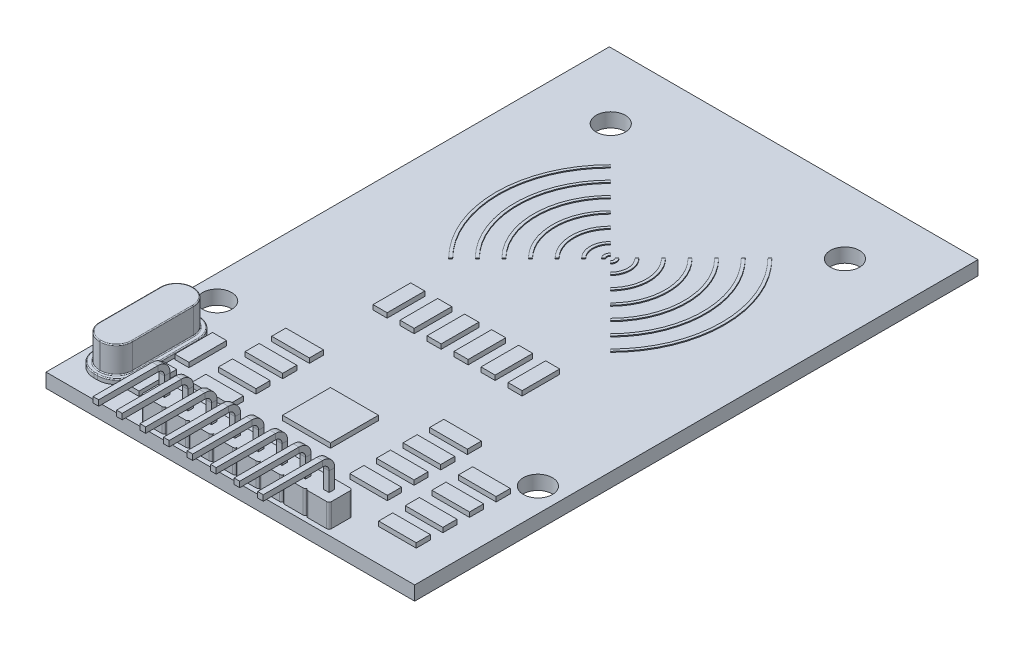
SolidWorks part; units mm, degrees
ref_plane "Front Plane" through (0, 0, 0) normal (0, 0, 1) x (1, 0, 0)
ref_plane "Top Plane" through (0, 0, 0) normal (0, 1, 0) x (1, 0, 0)
ref_plane "Right Plane" through (0, 0, 0) normal (1, 0, 0) x (0, 0, -1)
sketch "Sketch1" plane through (0, 0, 0) normal (0, 1, 0) x (1, 0, 0)
  line L1 (-19.6, 29.95) -> (19.6, 29.95)
  line L2 (-19.6, 29.95) -> (-19.6, -29.95)
  line L3 (-19.6, -29.95) -> (19.6, -29.95)
  line L4 (19.6, 29.95) -> (19.6, -29.95)
  line L5 (-19.6, 29.95) -> (19.6, -29.95) construction
  line L6 (-19.6, -29.95) -> (19.6, 29.95) construction
  point P0 (0, 0)
  dimension "D1" = 39.2
  dimension "D2" = 59.9
extrude "Boss-Extrude1" add sketch "Sketch1" along normal blind 1.5
sketch "Sketch3" plane through (0, 1.5, 0) normal (0, 1, 0) x (1, 0, 0)
  line L0 (0, 29.95) -> (0, -29.95) construction
  line L2 (19.6, 29.95) -> (-19.6, 29.95) construction
  line L3 (-17.05, -14.3) -> (17.05, -14.3) construction
  line L4 (-12.45, 22.95) -> (12.45, 22.95) construction
  line L5 (-19.6, -29.95) -> (19.6, -29.95) construction
  circle A0 centre (12.45, 22.95) radius 1.55
  circle A1 centre (-12.45, 22.95) radius 1.55
  circle A2 centre (17.05, -14.3) radius 1.55
  circle A3 centre (-17.05, -14.3) radius 1.55
  point P16 (0, 22.95)
  point P17 (0, -14.3)
  dimension "D1" = 3.1
  dimension "D2" = 12.45
  dimension "D3" = 7
  dimension "D6" = 17.05
  dimension "D7" = 15.65
extrude "Cut-Extrude1" cut sketch "Sketch3" against normal up to surface (1.5 mm away) up to face at (0, 0, 0)
sketch "Sketch4" plane through (0, 1.5, 0) normal (0, 1, 0) x (1, 0, 0)
  line L0 (-19.6, -29.95) -> (19.6, -29.95) construction
  line L1 (-9.75, -26.95) -> (-7.75, -26.95)
  line L2 (-10, -27.2) -> (-10, -29.2)
  line L3 (-9.75, -29.45) -> (-7.75, -29.45)
  line L5 (-19.6, 29.95) -> (-19.6, -29.95) construction
  line L7 (-7.25, -29.45) -> (-5.25, -29.45)
  line L9 (-7.25, -26.95) -> (-5.25, -26.95)
  line L11 (-4.75, -29.45) -> (-2.75, -29.45)
  line L13 (-4.75, -26.95) -> (-2.75, -26.95)
  line L15 (-2.25, -29.45) -> (-0.25, -29.45)
  line L17 (-2.25, -26.95) -> (-0.25, -26.95)
  line L19 (0.25, -29.45) -> (2.25, -29.45)
  line L21 (0.25, -26.95) -> (2.25, -26.95)
  line L23 (2.75, -29.45) -> (4.75, -29.45)
  line L25 (2.75, -26.95) -> (4.75, -26.95)
  line L27 (5.25, -29.45) -> (7.25, -29.45)
  line L29 (5.25, -26.95) -> (7.25, -26.95)
  line L30 (10, -27.2) -> (10, -29.2)
  line L31 (7.75, -29.45) -> (9.75, -29.45)
  line L33 (7.75, -26.95) -> (9.75, -26.95)
  line L34 (-7.5, -27.2) -> (-7.5, -29.2) [skipped]
  line L35 (-5, -27.2) -> (-5, -29.2) [skipped]
  line L36 (-2.5, -27.2) -> (-2.5, -29.2) [skipped]
  line L37 (0, -27.2) -> (0, -29.2) [skipped]
  line L38 (2.5, -27.2) -> (2.5, -29.2) [skipped]
  line L39 (5, -27.2) -> (5, -29.2) [skipped]
  line L40 (7.5, -27.2) -> (7.5, -29.2) [skipped]
  arc A1 (-7.75, -26.95) -> (-7.5, -27.2) centre (-7.75, -27.2) cw
  arc A2 (-7.5, -29.2) -> (-7.75, -29.45) centre (-7.75, -29.2) cw
  arc A3 (-9.75, -29.45) -> (-10, -29.2) centre (-9.75, -29.2) cw
  arc A4 (-10, -27.2) -> (-9.75, -26.95) centre (-9.75, -27.2) cw
  arc A5 (-5, -29.2) -> (-5.25, -29.45) centre (-5.25, -29.2) cw
  arc A6 (-7.25, -29.45) -> (-7.5, -29.2) centre (-7.25, -29.2) cw
  arc A7 (-7.5, -27.2) -> (-7.25, -26.95) centre (-7.25, -27.2) cw
  arc A8 (-5.25, -26.95) -> (-5, -27.2) centre (-5.25, -27.2) cw
  arc A10 (-2.5, -29.2) -> (-2.75, -29.45) centre (-2.75, -29.2) cw
  arc A11 (-4.75, -29.45) -> (-5, -29.2) centre (-4.75, -29.2) cw
  arc A12 (-5, -27.2) -> (-4.75, -26.95) centre (-4.75, -27.2) cw
  arc A13 (-2.75, -26.95) -> (-2.5, -27.2) centre (-2.75, -27.2) cw
  arc A15 (0, -29.2) -> (-0.25, -29.45) centre (-0.25, -29.2) cw
  arc A16 (-2.25, -29.45) -> (-2.5, -29.2) centre (-2.25, -29.2) cw
  arc A17 (-2.5, -27.2) -> (-2.25, -26.95) centre (-2.25, -27.2) cw
  arc A18 (-0.25, -26.95) -> (0, -27.2) centre (-0.25, -27.2) cw
  arc A20 (2.5, -29.2) -> (2.25, -29.45) centre (2.25, -29.2) cw
  arc A21 (0.25, -29.45) -> (0, -29.2) centre (0.25, -29.2) cw
  arc A22 (0, -27.2) -> (0.25, -26.95) centre (0.25, -27.2) cw
  arc A23 (2.25, -26.95) -> (2.5, -27.2) centre (2.25, -27.2) cw
  arc A25 (5, -29.2) -> (4.75, -29.45) centre (4.75, -29.2) cw
  arc A26 (2.75, -29.45) -> (2.5, -29.2) centre (2.75, -29.2) cw
  arc A27 (2.5, -27.2) -> (2.75, -26.95) centre (2.75, -27.2) cw
  arc A28 (4.75, -26.95) -> (5, -27.2) centre (4.75, -27.2) cw
  arc A30 (7.5, -29.2) -> (7.25, -29.45) centre (7.25, -29.2) cw
  arc A31 (5.25, -29.45) -> (5, -29.2) centre (5.25, -29.2) cw
  arc A32 (5, -27.2) -> (5.25, -26.95) centre (5.25, -27.2) cw
  arc A33 (7.25, -26.95) -> (7.5, -27.2) centre (7.25, -27.2) cw
  arc A35 (10, -29.2) -> (9.75, -29.45) centre (9.75, -29.2) cw
  arc A36 (7.75, -29.45) -> (7.5, -29.2) centre (7.75, -29.2) cw
  arc A37 (7.5, -27.2) -> (7.75, -26.95) centre (7.75, -27.2) cw
  arc A38 (9.75, -26.95) -> (10, -27.2) centre (9.75, -27.2) cw
  point P12 (-7.5, -26.95)
  point P17 (-10, -29.45)
  point P20 (-10, -26.95)
  dimension "D7" = 0.25
  dimension "D1" = 2.5
  dimension "D2" = 2.5
  dimension "D3" = 0.5
  dimension "D4" = 9.6
  dimension "D8" = 8
extrude "Boss-Extrude3" add sketch "Sketch4" along normal blind 2.5
sketch "Sketch5" plane through (0, 4, 0) normal (0, 1, 0) x (1, 0, 0)
  line L2 (-7.75, -26.95) -> (-9.75, -26.95) construction
  line L3 (-9.05, -27.9) -> (-8.45, -27.9)
  line L4 (-9.05, -27.9) -> (-9.05, -28.5)
  line L5 (-9.05, -28.5) -> (-8.45, -28.5)
  line L6 (-8.45, -27.9) -> (-8.45, -28.5)
  line L7 (-10, -27.2) -> (-10, -29.2) construction
  line L8 (-6.55, -27.9) -> (-5.95, -27.9)
  line L9 (-5.95, -27.9) -> (-5.95, -28.5)
  line L10 (-6.55, -28.5) -> (-5.95, -28.5)
  line L11 (-6.55, -27.9) -> (-6.55, -28.5)
  line L12 (-4.05, -27.9) -> (-3.45, -27.9)
  line L13 (-3.45, -27.9) -> (-3.45, -28.5)
  line L14 (-4.05, -28.5) -> (-3.45, -28.5)
  line L15 (-4.05, -27.9) -> (-4.05, -28.5)
  line L16 (-1.55, -27.9) -> (-0.95, -27.9)
  line L17 (-0.95, -27.9) -> (-0.95, -28.5)
  line L18 (-1.55, -28.5) -> (-0.95, -28.5)
  line L19 (-1.55, -27.9) -> (-1.55, -28.5)
  line L20 (0.95, -27.9) -> (1.55, -27.9)
  line L21 (1.55, -27.9) -> (1.55, -28.5)
  line L22 (0.95, -28.5) -> (1.55, -28.5)
  line L23 (0.95, -27.9) -> (0.95, -28.5)
  line L24 (3.45, -27.9) -> (4.05, -27.9)
  line L25 (4.05, -27.9) -> (4.05, -28.5)
  line L26 (3.45, -28.5) -> (4.05, -28.5)
  line L27 (3.45, -27.9) -> (3.45, -28.5)
  line L28 (5.95, -27.9) -> (6.55, -27.9)
  line L29 (6.55, -27.9) -> (6.55, -28.5)
  line L30 (5.95, -28.5) -> (6.55, -28.5)
  line L31 (5.95, -27.9) -> (5.95, -28.5)
  line L32 (8.45, -27.9) -> (9.05, -27.9)
  line L33 (9.05, -27.9) -> (9.05, -28.5)
  line L34 (8.45, -28.5) -> (9.05, -28.5)
  line L35 (8.45, -27.9) -> (8.45, -28.5)
  dimension "D1" = 0.6
  dimension "D2" = 0.6
  dimension "D3" = 0.95
  dimension "D4" = 0.95
  dimension "D5" = 8
extrude "Cut-Extrude2" cut sketch "Sketch5" against normal up to surface (4 mm away) up to face at (-17.05, 0, 15.85)
ref_plane "Plane1" through (0, -1, 0) normal (0, -1, 0) x (-1, 0, 0)
sketch "Sketch6" plane through (0, -1, 0) normal (0, -1, 0) x (-1, 0, 0)
  line L0 (6.55, -28.5) -> (5.95, -28.5)
  line L1 (9.05, -28.5) -> (8.45, -28.5)
  line L2 (9.05, -28.5) -> (9.05, -27.9)
  line L3 (9.05, -27.9) -> (8.45, -27.9)
  line L4 (8.45, -28.5) -> (8.45, -27.9)
  line L5 (5.95, -28.5) -> (5.95, -27.9)
  line L6 (6.55, -27.9) -> (5.95, -27.9)
  line L7 (6.55, -28.5) -> (6.55, -27.9)
  line L8 (4.05, -28.5) -> (3.45, -28.5)
  line L9 (3.45, -28.5) -> (3.45, -27.9)
  line L10 (4.05, -27.9) -> (3.45, -27.9)
  line L11 (4.05, -28.5) -> (4.05, -27.9)
  line L12 (1.55, -28.5) -> (0.95, -28.5)
  line L13 (0.95, -28.5) -> (0.95, -27.9)
  line L14 (1.55, -27.9) -> (0.95, -27.9)
  line L15 (1.55, -28.5) -> (1.55, -27.9)
  line L16 (-0.95, -28.5) -> (-1.55, -28.5)
  line L17 (-1.55, -28.5) -> (-1.55, -27.9)
  line L18 (-0.95, -27.9) -> (-1.55, -27.9)
  line L19 (-0.95, -28.5) -> (-0.95, -27.9)
  line L20 (-3.45, -28.5) -> (-4.05, -28.5)
  line L21 (-4.05, -28.5) -> (-4.05, -27.9)
  line L22 (-3.45, -27.9) -> (-4.05, -27.9)
  line L23 (-3.45, -28.5) -> (-3.45, -27.9)
  line L24 (-5.95, -28.5) -> (-6.55, -28.5)
  line L25 (-6.55, -28.5) -> (-6.55, -27.9)
  line L26 (-5.95, -27.9) -> (-6.55, -27.9)
  line L27 (-5.95, -28.5) -> (-5.95, -27.9)
  line L28 (-8.45, -28.5) -> (-9.05, -28.5)
  line L29 (-9.05, -28.5) -> (-9.05, -27.9)
  line L30 (-8.45, -27.9) -> (-9.05, -27.9)
  line L31 (-8.45, -28.5) -> (-8.45, -27.9)
  dimension "D1" = 8
sketch "Sketch7" plane through (-10, 0, 0) normal (-1, 0, 0) x (0, 0, 1)
  line L0 (28.2, -1) -> (28.2, 6)
  line L1 (28.5, -1) -> (27.9, -1) construction
  line L2 (29.2, 7) -> (35.5, 7)
  arc A0 (29.2, 7) -> (28.2, 6) centre (29.2, 6) ccw
  point P7 (28.2, 7)
  dimension "D3" = 1
  dimension "D1" = 7.3
  dimension "D2" = 8
sweep "Sweep1" add profiles "Sketch6" path "Sketch7"
sketch "Sketch8" plane through (0, 1.5, 0) normal (0, 1, 0) x (1, 0, 0)
  line L0 (-19.6, -29.95) -> (19.6, -29.95) construction
  line L1 (-16.5, -17.15) -> (-16.15, -17.15)
  line L2 (-18.6, -19.25) -> (-18.6, -25.85)
  line L3 (-16.5, -27.95) -> (-16.15, -27.95)
  line L4 (-14.05, -19.25) -> (-14.05, -25.85)
  line L6 (-19.6, 29.95) -> (-19.6, -29.95) construction
  arc A0 (-18.6, -25.85) -> (-16.5, -27.95) centre (-16.5, -25.85) ccw
  arc A1 (-16.15, -27.95) -> (-14.05, -25.85) centre (-16.15, -25.85) ccw
  arc A2 (-16.15, -17.15) -> (-14.05, -19.25) centre (-16.15, -19.25) cw
  arc A3 (-16.5, -17.15) -> (-18.6, -19.25) centre (-16.5, -19.25) ccw
  point P6 (-18.6, -27.95)
  point P11 (-14.05, -17.15)
  point P14 (-18.6, -17.15)
  dimension "D3" = 2.1
  dimension "D1" = 10.8
  dimension "D2" = 4.55
  dimension "D4" = 1
  dimension "D5" = 2
extrude "Boss-Extrude4" add sketch "Sketch8" along normal blind 0.5
sketch "Sketch10" plane through (0, 2, 0) normal (0, 1, 0) x (1, 0, 0)
  line L0 (-16.325, -17.15) -> (-16.325, -27.95) construction
  line L1 (-16.15, -17.15) -> (-16.5, -17.15) construction
  line L2 (-16.5, -27.95) -> (-16.15, -27.95) construction
  line L3 (-18.6, -22.55) -> (-14.05, -22.55) construction
  line L4 (-18.6, -19.25) -> (-18.6, -25.85) construction
  line L5 (-14.05, -25.85) -> (-14.05, -19.25) construction
  line L7 (-16.375, -17.6) -> (-16.275, -17.6)
  line L8 (-18.075, -19.3) -> (-18.075, -25.8)
  line L9 (-16.375, -27.5) -> (-16.275, -27.5)
  line L10 (-14.575, -19.3) -> (-14.575, -25.8)
  line L11 (-18.075, -17.6) -> (-14.575, -27.5) construction
  line L12 (-18.075, -27.5) -> (-14.575, -17.6) construction
  arc A0 (-18.075, -25.8) -> (-16.375, -27.5) centre (-16.375, -25.8) ccw
  arc A1 (-16.275, -27.5) -> (-14.575, -25.8) centre (-16.275, -25.8) ccw
  arc A2 (-14.575, -19.3) -> (-16.275, -17.6) centre (-16.275, -19.3) ccw
  arc A3 (-16.375, -17.6) -> (-18.075, -19.3) centre (-16.375, -19.3) ccw
  point P12 (-16.325, -22.55)
  dimension "D3" = 1.7
  dimension "D1" = 3.5
  dimension "D2" = 9.9
extrude "Boss-Extrude5" add sketch "Sketch10" along normal blind 2.8
fillet "Fillet1" radius 0.1 24 edges at (-17.5771, 4.8, 18.0979) (-16.325, 4.8, 17.6) (-15.0729, 4.8, 18.0979) (-14.575, 4.8, 22.55) (-15.0729, 4.8, 27.0021) (-16.325, 4.8, 27.5) (-17.5771, 4.8, 27.0021) (-17.5771, 2, 18.0979) (-16.325, 2, 17.6) (-15.0729, 2, 18.0979) (-14.575, 2, 22.55) (-15.0729, 2, 27.0021) (-16.325, 2, 27.5) (-17.5771, 2, 27.0021) (-17.9849, 2, 17.7651) (-16.325, 2, 17.15) (-14.6651, 2, 17.7651) (-14.05, 2, 22.55) (-14.6651, 2, 27.3349) (-16.325, 2, 27.95) (-17.9849, 2, 27.3349) (-18.075, 4.8, 22.55) (-18.075, 2, 22.55) (-18.6, 2, 22.55)
sketch "Sketch11" plane through (0, 1.5, 0) normal (0, 1, 0) x (1, 0, 0)
  line L0 (-0.2475, 10.6975) -> (-0.4596, 10.9096)
  line L1 (-0.35, 10.45) -> (-19.6, 10.45) construction
  line L2 (-19.6, 29.95) -> (-19.6, -29.95) construction
  line L3 (19.6, 29.95) -> (-19.6, 29.95) construction
  line L4 (0.2475, 10.6975) -> (0.4596, 10.9096)
  line L5 (-0.2475, 10.2025) -> (-0.4596, 9.9904)
  line L6 (0.2475, 10.2025) -> (0.4596, 9.9904)
  line L7 (-8.4853, 18.9353) -> (-8.5913, 19.0413)
  line L8 (-8.5913, 1.8587) -> (-8.4853, 1.9647)
  line L9 (8.4853, 1.9647) -> (8.5913, 1.8587)
  line L10 (8.4853, 18.9353) -> (8.5913, 19.0413)
  line L11 (-8.3792, 18.8292) -> (-8.4853, 18.9353)
  line L12 (-6.965, 17.415) -> (-7.1771, 17.6271)
  line L13 (-5.5508, 16.0008) -> (-5.7629, 16.2129)
  line L14 (-4.1366, 14.5866) -> (-4.3487, 14.7987)
  line L15 (-2.7224, 13.1724) -> (-2.9345, 13.3845)
  line L16 (-1.3081, 11.7581) -> (-1.5203, 11.9703)
  line L17 (-1.3081, 9.1419) -> (-1.5203, 8.9297)
  line L18 (-2.7224, 7.7276) -> (-2.9345, 7.5155)
  line L19 (-4.1366, 6.3134) -> (-4.3487, 6.1013)
  line L20 (-5.5508, 4.8992) -> (-5.7629, 4.6871)
  line L21 (-8.3792, 2.0708) -> (-8.4853, 1.9647)
  line L22 (1.3081, 9.1419) -> (1.5203, 8.9297)
  line L23 (2.7224, 7.7276) -> (2.9345, 7.5155)
  line L24 (4.1366, 6.3134) -> (4.3487, 6.1013)
  line L25 (5.5508, 4.8992) -> (5.7629, 4.6871)
  line L26 (6.965, 3.485) -> (7.1771, 3.2729)
  line L27 (8.3792, 2.0708) -> (8.4853, 1.9647)
  line L28 (1.3081, 11.7581) -> (1.5203, 11.9703)
  line L29 (2.7224, 13.1724) -> (2.9345, 13.3845)
  line L30 (4.1366, 14.5866) -> (4.3487, 14.7987)
  line L31 (5.5508, 16.0008) -> (5.7629, 16.2129)
  line L32 (6.965, 17.415) -> (7.1771, 17.6271)
  line L33 (8.3792, 18.8292) -> (8.4853, 18.9353)
  line L34 (-6.965, 3.485) -> (-7.1771, 3.2729)
  line L35 (0, 10.45) -> (0, 29.95) construction
  arc A0 (-0.3536, 10.8036) -> (-0.3536, 10.0964) centre (0, 10.45) ccw construction
  arc A1 (-1.4142, 11.8642) -> (-1.4142, 9.0358) centre (0, 10.45) ccw construction
  arc A2 (-2.8284, 13.2784) -> (-2.8284, 7.6216) centre (0, 10.45) ccw construction
  arc A3 (-4.2426, 14.6926) -> (-4.2426, 6.2074) centre (0, 10.45) ccw construction
  arc A4 (-5.6569, 16.1069) -> (-5.6569, 4.7931) centre (0, 10.45) ccw construction
  arc A5 (-5.6569, 16.1069) -> (-5.6569, 4.7931) centre (0, 10.45) ccw
  arc A6 (-7.0711, 17.5211) -> (-7.0711, 3.3789) centre (0, 10.45) ccw construction
  arc A7 (-8.4853, 18.9353) -> (-8.4853, 1.9647) centre (0, 10.45) ccw construction
  arc A8 (0.3536, 10.0964) -> (0.3536, 10.8036) centre (0, 10.45) ccw construction
  arc A9 (1.4142, 9.0358) -> (1.4142, 11.8642) centre (0, 10.45) ccw construction
  arc A10 (2.8284, 7.6216) -> (2.8284, 13.2784) centre (0, 10.45) ccw construction
  arc A11 (4.2426, 6.2074) -> (4.2426, 14.6926) centre (0, 10.45) ccw construction
  arc A12 (5.6569, 4.7931) -> (5.6569, 16.1069) centre (0, 10.45) ccw construction
  arc A13 (5.6569, 4.7931) -> (5.6569, 16.1069) centre (0, 10.45) ccw
  arc A14 (7.0711, 3.3789) -> (7.0711, 17.5211) centre (0, 10.45) ccw construction
  arc A15 (8.4853, 1.9647) -> (8.4853, 18.9353) centre (0, 10.45) ccw construction
  arc A16 (-8.5913, 19.0413) -> (-8.5913, 1.8587) centre (0, 10.45) ccw
  arc A17 (-7.1771, 17.6271) -> (-7.1771, 3.2729) centre (0, 10.45) ccw
  arc A18 (-5.7629, 16.2129) -> (-5.7629, 4.6871) centre (0, 10.45) ccw
  arc A19 (-4.3487, 14.7987) -> (-4.3487, 6.1013) centre (0, 10.45) ccw
  arc A20 (-2.9345, 13.3845) -> (-2.9345, 7.5155) centre (0, 10.45) ccw
  arc A21 (-1.5203, 11.9703) -> (-1.5203, 8.9297) centre (0, 10.45) ccw
  arc A22 (-0.4596, 10.9096) -> (-0.4596, 9.9904) centre (0, 10.45) ccw
  arc A23 (0.4596, 9.9904) -> (0.4596, 10.9096) centre (0, 10.45) ccw
  arc A24 (1.5203, 8.9297) -> (1.5203, 11.9703) centre (0, 10.45) ccw
  arc A25 (2.9345, 7.5155) -> (2.9345, 13.3845) centre (0, 10.45) ccw
  arc A26 (4.3487, 6.1013) -> (4.3487, 14.7987) centre (0, 10.45) ccw
  arc A27 (5.7629, 4.6871) -> (5.7629, 16.2129) centre (0, 10.45) ccw
  arc A28 (7.1771, 3.2729) -> (7.1771, 17.6271) centre (0, 10.45) ccw
  arc A29 (8.5913, 1.8587) -> (8.5913, 19.0413) centre (0, 10.45) ccw
  arc A30 (-8.3792, 18.8292) -> (-8.3792, 2.0708) centre (0, 10.45) ccw
  arc A31 (-6.965, 17.415) -> (-6.965, 3.485) centre (0, 10.45) ccw
  arc A32 (-5.5508, 16.0008) -> (-5.5508, 4.8992) centre (0, 10.45) ccw
  arc A33 (-4.1366, 14.5866) -> (-4.1366, 6.3134) centre (0, 10.45) ccw
  arc A34 (-2.7224, 13.1724) -> (-2.7224, 7.7276) centre (0, 10.45) ccw
  arc A35 (-1.3081, 11.7581) -> (-1.3081, 9.1419) centre (0, 10.45) ccw
  arc A36 (-0.2475, 10.6975) -> (-0.2475, 10.2025) centre (0, 10.45) ccw
  arc A37 (0.2475, 10.2025) -> (0.2475, 10.6975) centre (0, 10.45) ccw
  arc A38 (1.3081, 9.1419) -> (1.3081, 11.7581) centre (0, 10.45) ccw
  arc A39 (2.7224, 7.7276) -> (2.7224, 13.1724) centre (0, 10.45) ccw
  arc A40 (4.1366, 6.3134) -> (4.1366, 14.5866) centre (0, 10.45) ccw
  arc A41 (5.5508, 4.8992) -> (5.5508, 16.0008) centre (0, 10.45) ccw
  arc A42 (6.965, 3.485) -> (6.965, 17.415) centre (0, 10.45) ccw
  arc A43 (8.3792, 2.0708) -> (8.3792, 18.8292) centre (0, 10.45) ccw
  dimension "D1" = 45
  dimension "D2" = 0.5
  dimension "D3" = 2
  dimension "D4" = 6
  dimension "D5" = 10
  dimension "D6" = 19.5
  dimension "D10" = 8
  dimension "D11" = 4
  dimension "D12" = 12
  dimension "D7" = 45
  dimension "D8" = 45
  dimension "D9" = 45
  dimension "D13" = 0.15
  dimension "D14" = 0.15
extrude "Boss-Extrude6" add sketch "Sketch11" along normal blind 0.1 contours A16 L8 L21 A30 L11 L7 | A17 L34 A31 L12 | A18 L20 A32 L13 | A19 L19 A33 L14 | A20 L18 A34 L15 | A35 L17 A21 L16 | A36 L5 A22 L0 | A23 L4 A37 L6 | A24 L28 A38 L22 | A25 L29 A39 L23 | A26 L30 A40 L24 | A27 L31 A41 L25 | A28 L32 A42 L26 | A29 L10 L33 A43 L27 L9
sketch "Esboço1" plane through (0, 1.5, 0) normal (0, 1, 0) x (1, 0, 0)
  line L0 (6.425, -4.85) -> (5.055, -4.85) construction
  line L1 (6.425, -2.85) -> (7.925, -2.85)
  line L2 (6.425, -2.85) -> (6.425, -6.85)
  line L3 (6.425, -6.85) -> (7.925, -6.85)
  line L4 (7.925, -2.85) -> (7.925, -6.85)
  line L5 (3.555, -4.85) -> (2.185, -4.85) construction
  line L6 (5.055, -2.85) -> (3.555, -2.85)
  line L7 (5.055, -2.85) -> (5.055, -6.85)
  line L8 (5.055, -6.85) -> (3.555, -6.85)
  line L9 (3.555, -2.85) -> (3.555, -6.85)
  line L10 (2.185, -2.85) -> (0.685, -2.85)
  line L11 (2.185, -2.85) -> (2.185, -6.85)
  line L12 (2.185, -6.85) -> (0.685, -6.85)
  line L13 (0.685, -2.85) -> (0.685, -6.85)
  line L14 (-0.685, -2.85) -> (-2.185, -2.85)
  line L15 (-0.685, -2.85) -> (-0.685, -6.85)
  line L16 (-0.685, -6.85) -> (-2.185, -6.85)
  line L17 (-2.185, -2.85) -> (-2.185, -6.85)
  line L18 (-3.555, -2.85) -> (-5.055, -2.85)
  line L19 (-3.555, -2.85) -> (-3.555, -6.85)
  line L20 (-3.555, -6.85) -> (-5.055, -6.85)
  line L21 (-5.055, -2.85) -> (-5.055, -6.85)
  line L22 (-6.425, -2.85) -> (-7.925, -2.85)
  line L23 (-6.425, -2.85) -> (-6.425, -6.85)
  line L24 (-6.425, -6.85) -> (-7.925, -6.85)
  line L25 (-7.925, -2.85) -> (-7.925, -6.85)
  line L26 (-8.4, -22.15) -> (-8.4, -20.8167) construction
  line L27 (0.685, -4.85) -> (-0.685, -4.85) construction
  line L28 (-8.4, -19.3167) -> (-8.4, -17.9833) construction
  line L29 (-2.185, -4.85) -> (-3.555, -4.85) construction
  line L30 (-8.4, -16.4833) -> (-8.4, -15.15) construction
  line L31 (-5.055, -4.85) -> (-6.425, -4.85) construction
  line L32 (0, 0) -> (0, -18.65) construction
  line L33 (19.6, 29.95) -> (-19.6, 29.95) construction
  line L34 (8.4, -22.15) -> (8.4, -20.8167) construction
  line L35 (-10.4, -23.65) -> (-6.4, -23.65)
  line L36 (-10.4, -23.65) -> (-10.4, -22.15)
  line L37 (-10.4, -22.15) -> (-6.4, -22.15)
  line L38 (-6.4, -23.65) -> (-6.4, -22.15)
  line L39 (-10.4, -19.3167) -> (-6.4, -19.3167)
  line L40 (-10.4, -19.3167) -> (-10.4, -20.8167)
  line L41 (-10.4, -20.8167) -> (-6.4, -20.8167)
  line L42 (-6.4, -19.3167) -> (-6.4, -20.8167)
  line L43 (-10.4, -16.4833) -> (-6.4, -16.4833)
  line L44 (-10.4, -16.4833) -> (-10.4, -17.9833)
  line L45 (-10.4, -17.9833) -> (-6.4, -17.9833)
  line L46 (-6.4, -16.4833) -> (-6.4, -17.9833)
  line L47 (-10.4, -13.65) -> (-6.4, -13.65)
  line L48 (-10.4, -13.65) -> (-10.4, -15.15)
  line L49 (-10.4, -15.15) -> (-6.4, -15.15)
  line L50 (-6.4, -13.65) -> (-6.4, -15.15)
  line L51 (6.4, -13.65) -> (10.4, -13.65)
  line L52 (6.4, -13.65) -> (6.4, -15.15)
  line L53 (6.4, -15.15) -> (10.4, -15.15)
  line L54 (10.4, -13.65) -> (10.4, -15.15)
  line L55 (6.4, -16.4833) -> (10.4, -16.4833)
  line L56 (6.4, -16.4833) -> (6.4, -17.9833)
  line L57 (6.4, -17.9833) -> (10.4, -17.9833)
  line L58 (10.4, -16.4833) -> (10.4, -17.9833)
  line L59 (6.4, -19.3167) -> (10.4, -19.3167)
  line L60 (6.4, -19.3167) -> (6.4, -20.8167)
  line L61 (6.4, -20.8167) -> (10.4, -20.8167)
  line L62 (10.4, -19.3167) -> (10.4, -20.8167)
  line L63 (6.4, -22.15) -> (10.4, -22.15)
  line L64 (6.4, -22.15) -> (6.4, -23.65)
  line L65 (6.4, -23.65) -> (10.4, -23.65)
  line L66 (10.4, -22.15) -> (10.4, -23.65)
  line L67 (8.4, -19.3167) -> (8.4, -17.9833) construction
  line L68 (-8.4, -18.65) -> (8.4, -18.65) construction
  line L69 (8.4, -16.4833) -> (8.4, -15.15) construction
  line L70 (-19.6, 29.95) -> (-19.6, -29.95) construction
  line L71 (-13.15, -21.95) -> (-13.15, -23.25) construction
  line L72 (-13.9, -17.95) -> (-12.4, -17.95)
  line L73 (-13.9, -17.95) -> (-13.9, -21.95)
  line L74 (-13.9, -21.95) -> (-12.4, -21.95)
  line L75 (-12.4, -17.95) -> (-12.4, -21.95)
  line L76 (-13.9, -23.25) -> (-12.4, -23.25)
  line L77 (-13.9, -23.25) -> (-13.9, -27.25)
  line L78 (-13.9, -27.25) -> (-12.4, -27.25)
  line L79 (-12.4, -23.25) -> (-12.4, -27.25)
  line L80 (-19.6, -29.95) -> (19.6, -29.95) construction
  line L81 (14.3, -17.9833) -> (14.3, -19.3167) construction
  line L82 (12.3, -16.4833) -> (16.3, -16.4833)
  line L83 (12.3, -16.4833) -> (12.3, -17.9833)
  line L84 (12.3, -17.9833) -> (16.3, -17.9833)
  line L85 (16.3, -16.4833) -> (16.3, -17.9833)
  line L86 (12.3, -19.3167) -> (16.3, -19.3167)
  line L87 (12.3, -19.3167) -> (12.3, -20.8167)
  line L88 (12.3, -20.8167) -> (16.3, -20.8167)
  line L89 (16.3, -19.3167) -> (16.3, -20.8167)
  line L90 (12.3, -22.15) -> (16.3, -22.15)
  line L91 (12.3, -22.15) -> (12.3, -23.65)
  line L92 (12.3, -23.65) -> (16.3, -23.65)
  line L93 (16.3, -22.15) -> (16.3, -23.65)
  line L94 (12.3, -24.9833) -> (16.3, -24.9833)
  line L95 (12.3, -24.9833) -> (12.3, -26.4833)
  line L96 (12.3, -26.4833) -> (16.3, -26.4833)
  line L97 (16.3, -24.9833) -> (16.3, -26.4833)
  line L98 (14.3, -20.8167) -> (14.3, -22.15) construction
  line L99 (14.3, -23.65) -> (14.3, -24.9833) construction
  line L100 (19.6, -29.95) -> (19.6, 29.95) construction
  point P34 (0, -4.85)
  point P86 (0, -18.65)
  point P123 (17.324, -17.9833)
  dimension "D1" = 1.5
  dimension "D2" = 4
  dimension "D3" = 1.37
  dimension "D4" = 32.8
  dimension "D5" = 43.6
  dimension "D6" = 10
  dimension "D7" = 9.2
  dimension "D8" = 9.3
  dimension "D9" = 7.2
  dimension "D10" = 12
  dimension "D11" = 3.3
extrude "Ressalto-extrusão1" add sketch "Esboço1" along normal blind 0.5
sketch "Esboço2" plane through (0, 1.5, 0) normal (0, 1, 0) x (1, 0, 0)
  line L0 (0, 0) -> (0, -16.75) construction
  line L1 (-2.55, -16.75) -> (2.55, -16.75)
  line L2 (-2.55, -16.75) -> (-2.55, -21.85)
  line L3 (-2.55, -21.85) -> (2.55, -21.85)
  line L4 (2.55, -16.75) -> (2.55, -21.85)
  line L5 (19.6, 29.95) -> (-19.6, 29.95) construction
  dimension "D1" = 5.1
  dimension "D2" = 46.7
extrude "Ressalto-extrusão2" add sketch "Esboço2" along normal blind 0.5
